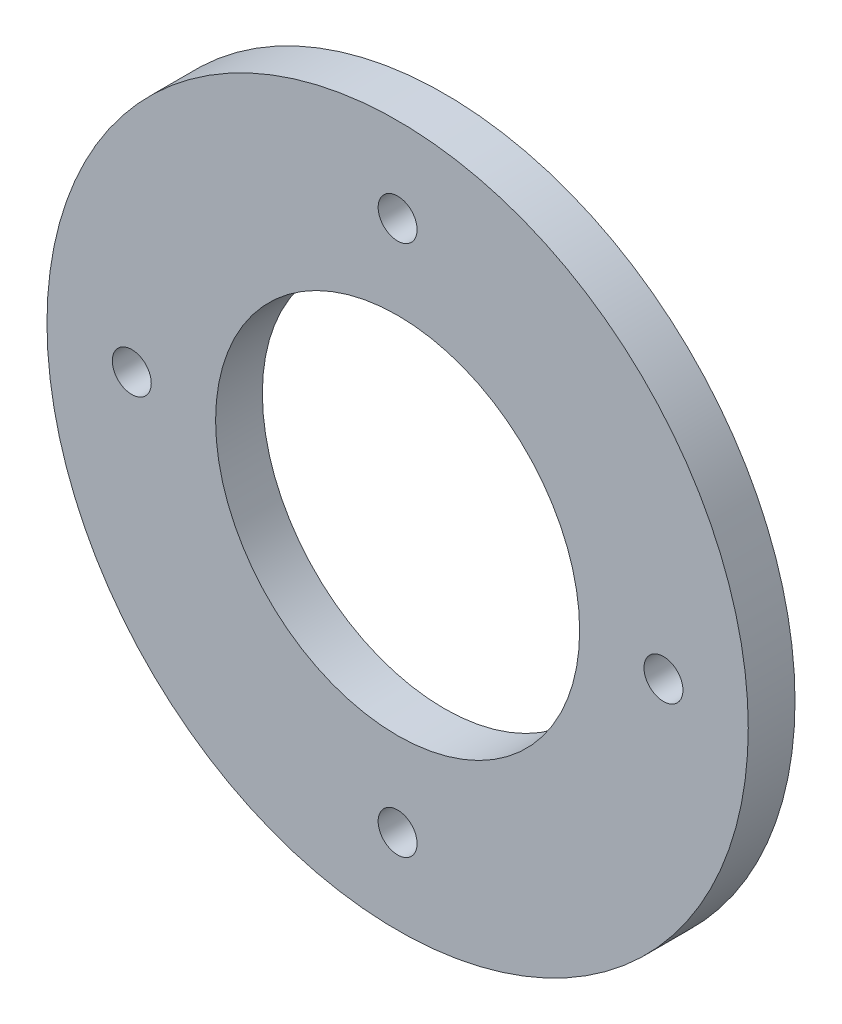
SolidWorks part; units mm, degrees
ref_plane "Alzado" through (0, 0, 0) normal (0, 0, 1) x (1, 0, 0)
ref_plane "Planta" through (0, 0, 0) normal (0, 1, 0) x (1, 0, 0)
ref_plane "Vista lateral" through (0, 0, 0) normal (1, 0, 0) x (0, 0, -1)
sketch "Croquis1" plane through (0, 0, 0) normal (0, 0, 1) x (1, 0, 0)
  line L0 (0, -22.5) -> (0, 22.5) construction
  line L1 (-22.5, 0) -> (22.5, 0) construction
  circle A0 centre (0, 0) radius 11.68
  circle A1 centre (0, 0) radius 17.0578 construction
  circle A3 centre (0, 0) radius 22.5
  circle A4 centre (-17.0578, 0) radius 1.25
  circle A5 centre (0, 17.0578) radius 1.25
  circle A6 centre (17.0578, 0) radius 1.25
  circle A7 centre (0, -17.0578) radius 1.25
  point P8 (0, 0)
  point P11 (0, 0)
  dimension "D1" = 23.36
  dimension "D2" = 45
  dimension "D3" = 2.5
extrude "Saliente-Extruir1" add sketch "Croquis1" along normal blind 3
